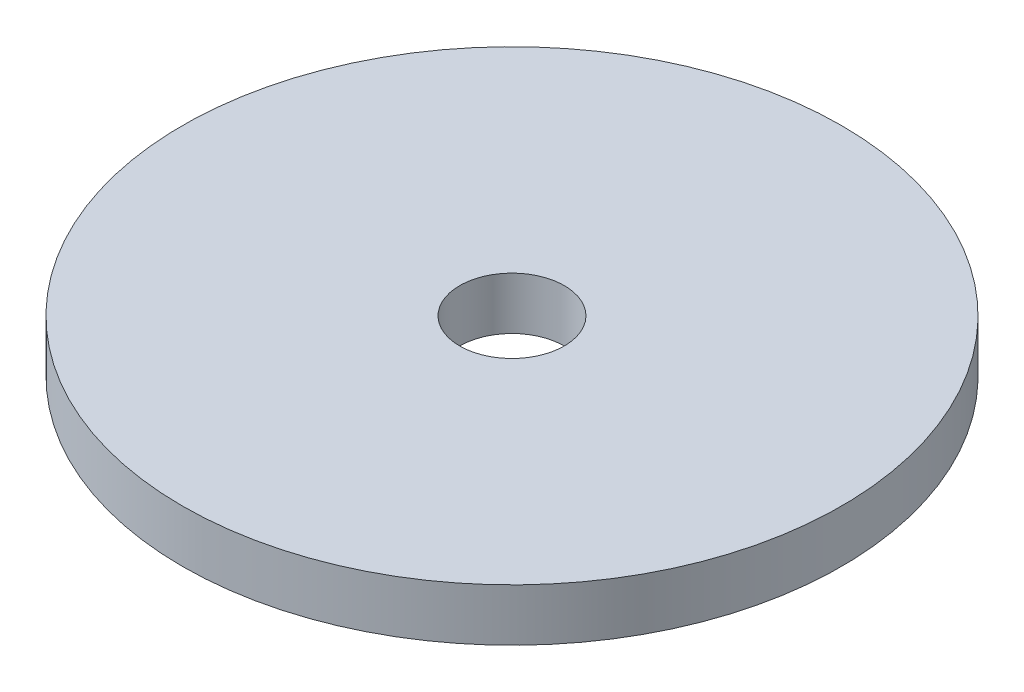
SolidWorks part; units mm, degrees
material "Acrylic (Medium-high impact)"
ref_plane "Front Plane" through (0, 0, 0) normal (0, 0, 1) x (1, 0, 0)
ref_plane "Top Plane" through (0, 0, 0) normal (0, 1, 0) x (1, 0, 0)
ref_plane "Right Plane" through (0, 0, 0) normal (1, 0, 0) x (0, 0, -1)
sketch "Sketch1" plane through (0, 0, 0) normal (0, 1, 0) x (1, 0, 0)
  circle A0 centre (0, 0) radius 20
  circle A1 centre (0, 0) radius 3.175
  dimension "D1" = 40
  dimension "D2" = 6.35
extrude "Boss-Extrude1" add sketch "Sketch1" along normal blind 3.175
